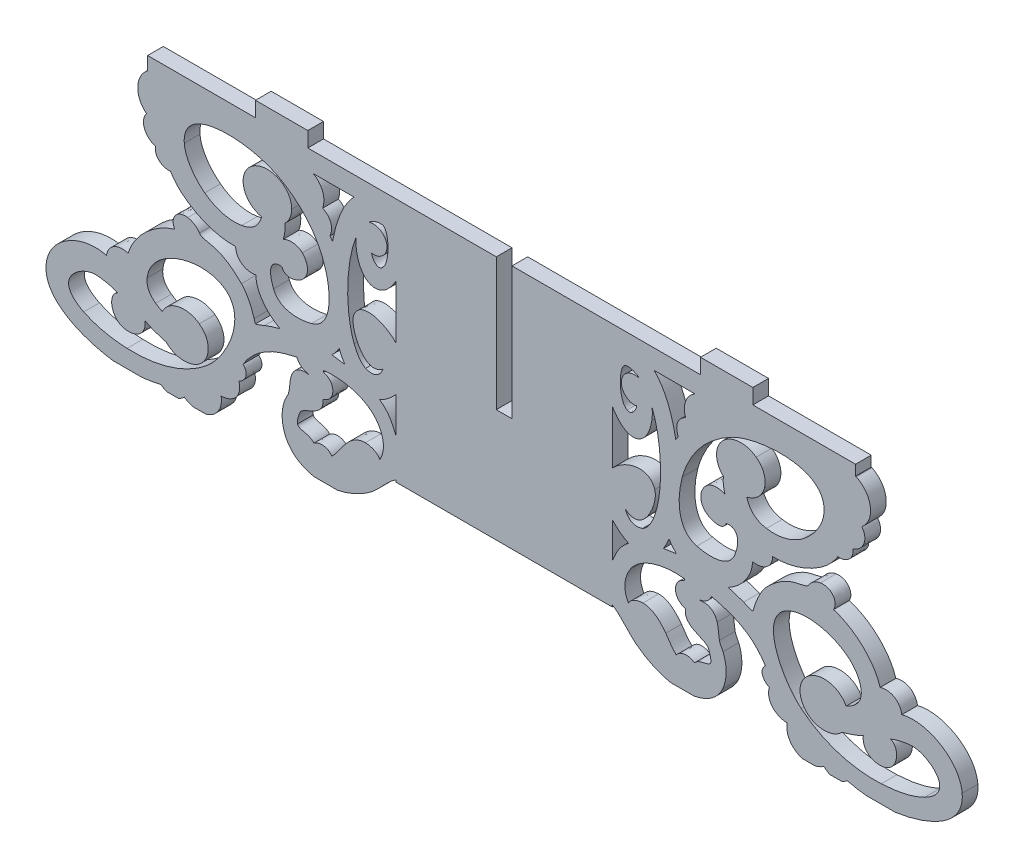
SolidWorks part; units mm, degrees
ref_plane "Plano frontal" through (0, 0, 0) normal (0, 0, 1) x (1, 0, 0)
ref_plane "Plano superior" through (0, 0, 0) normal (0, 1, 0) x (1, 0, 0)
ref_plane "Plano direito" through (0, 0, 0) normal (1, 0, 0) x (0, 0, -1)
sketch "Model" plane through (0, 0, 0) normal (0, 0, 1) x (1, 0, 0)
  line L0 (-5.6284, -112.7453) -> (-5.6464, -112.5024)
  line L1 (-13.1021, -117.3563) -> (-16.0542, -117.3569)
  line L2 (-18.281, -105.2638) -> (-19.6289, -105.6073)
  line L3 (-29.8849, -117.352) -> (-31.4771, -117.3528)
  line L4 (-33.3867, -117.362) -> (-34.8157, -117.362)
  line L5 (-37.9546, -117.362) -> (-41.6837, -117.3591)
  line L6 (-37.2753, -83.1991) -> (-37.2753, -81.5107)
  line L7 (-37.2753, -81.5107) -> (-23.5478, -81.5107)
  line L8 (-23.5478, -81.5107) -> (-23.5478, -79.5846)
  line L9 (-23.5478, -79.5846) -> (-16.8811, -79.5846)
  line L10 (-16.8811, -79.5846) -> (-16.8811, -81.5107)
  line L11 (-16.8811, -81.5107) -> (7.1189, -81.5107)
  line L12 (7.1189, -81.5107) -> (7.1189, -98.3678)
  line L13 (7.1189, -98.3678) -> (9.1189, -98.3678)
  line L14 (9.1189, -98.3678) -> (9.1189, -81.5107)
  line L15 (9.1189, -81.5107) -> (33.1189, -81.5107)
  line L16 (33.1189, -81.5107) -> (33.1189, -79.5846)
  line L17 (33.1189, -79.5846) -> (39.7856, -79.5846)
  line L18 (39.7856, -79.5846) -> (39.7856, -81.5107)
  line L19 (39.7856, -81.5107) -> (52.8602, -81.5107)
  line L20 (52.8602, -81.5107) -> (52.8602, -82.8287)
  line L21 (52.8602, -82.8287) -> (52.8959, -82.8287)
  line L22 (52.8959, -82.8287) -> (52.9623, -82.861)
  line L23 (57.9215, -117.3591) -> (54.1924, -117.362)
  line L24 (51.0535, -117.362) -> (49.6245, -117.362)
  line L25 (47.7148, -117.3528) -> (46.1226, -117.352)
  line L26 (35.8666, -105.6073) -> (34.5187, -105.2638)
  line L27 (32.2919, -117.3569) -> (29.3398, -117.3563)
  line L28 (21.8841, -112.5024) -> (21.8661, -112.7453)
  line L29 (-10.9876, -83.9801) -> (-16.2025, -83.9801)
  line L30 (32.4403, -83.9801) -> (27.2253, -83.9801)
  line L31 (21.8983, -107.6195) -> (21.8983, -103.0943)
  line L32 (21.8983, -97.4057) -> (21.8983, -90.5812)
  line L33 (30.061, -102.7829) -> (28.4015, -103.0293)
  line L34 (-5.6605, -107.6195) -> (-5.6605, -103.0943)
  line L35 (-5.6605, -97.4057) -> (-5.6605, -90.5812)
  line L36 (-13.8232, -102.7829) -> (-12.1638, -103.0293)
  spline S0 degree 3 poles (-5.6464, -112.5024) (-6.5419, -112.9865) (-7.8893, -114.6814) (-8.6517, -115.2757) knots 0.009901 0.009901 0.009901 0.009901 0.019802 0.019802 0.019802 0.019802
  spline S1 degree 3 poles (-8.6517, -115.2757) (-9.9492, -116.2871) (-11.4791, -117.04) (-13.1021, -117.3563) knots 0.019802 0.019802 0.019802 0.019802 0.029703 0.029703 0.029703 0.029703
  spline S2 degree 3 poles (-16.0542, -117.3569) (-17.6074, -117.0704) (-18.9753, -116.2771) (-19.6727, -114.8027) knots 0.039604 0.039604 0.039604 0.039604 0.049505 0.049505 0.049505 0.049505
  spline S3 degree 3 poles (-19.6727, -114.8027) (-20.2748, -113.5296) (-20.309, -111.9264) (-19.7445, -110.6272) knots 0.049505 0.049505 0.049505 0.049505 0.059406 0.059406 0.059406 0.059406
  spline S4 degree 3 poles (-19.7445, -110.6272) (-19.5924, -110.2771) (-19.3699, -109.9824) (-19.2888, -109.595) knots 0.059406 0.059406 0.059406 0.059406 0.069307 0.069307 0.069307 0.069307
  spline S5 degree 3 poles (-19.2888, -109.595) (-19.1614, -108.9856) (-19.1819, -108.3312) (-18.999, -107.7315) knots 0.069307 0.069307 0.069307 0.069307 0.079208 0.079208 0.079208 0.079208
  spline S6 degree 3 poles (-18.999, -107.7315) (-18.6689, -106.6497) (-17.8333, -106.246) (-16.8102, -106.4384) knots 0.079208 0.079208 0.079208 0.079208 0.089109 0.089109 0.089109 0.089109
  spline S7 degree 3 poles (-16.8102, -106.4384) (-16.8066, -106.4196) (-16.8024, -106.4007) (-16.7979, -106.3817) knots 0.089109 0.089109 0.089109 0.089109 0.09901 0.09901 0.09901 0.09901
  spline S8 degree 3 poles (-16.7979, -106.3817) (-17.4996, -106.2832) (-17.9964, -105.8964) (-18.281, -105.2638) knots 0.09901 0.09901 0.09901 0.09901 0.108911 0.108911 0.108911 0.108911
  spline S9 degree 3 poles (-19.6289, -105.6073) (-21.9055, -106.2199) (-23.8126, -107.3723) (-25.137, -109.472) knots 0.118812 0.118812 0.118812 0.118812 0.128713 0.128713 0.128713 0.128713
  spline S10 degree 3 poles (-25.137, -109.472) (-24.3471, -110.1811) (-24.768, -111.1844) (-25.6484, -111.6117) knots 0.128713 0.128713 0.128713 0.128713 0.138614 0.138614 0.138614 0.138614
  spline S11 degree 3 poles (-25.6484, -111.6117) (-25.2197, -113.1217) (-26.2828, -114.3014) (-27.9206, -114.3964) knots 0.138614 0.138614 0.138614 0.138614 0.148515 0.148515 0.148515 0.148515
  spline S12 degree 3 poles (-27.9206, -114.3964) (-27.6704, -115.807) (-28.5691, -117.0098) (-29.8849, -117.352) knots 0.148515 0.148515 0.148515 0.148515 0.158416 0.158416 0.158416 0.158416
  spline S13 degree 3 poles (-31.4771, -117.3528) (-31.8723, -117.2547) (-32.2526, -117.0856) (-32.6065, -116.8521) knots 0.168317 0.168317 0.168317 0.168317 0.178218 0.178218 0.178218 0.178218
  spline S14 degree 3 poles (-32.6065, -116.8521) (-32.7813, -117.0214) (-33.1597, -117.3166) (-33.3867, -117.362) knots 0.178218 0.178218 0.178218 0.178218 0.188119 0.188119 0.188119 0.188119
  spline S15 degree 3 poles (-34.8157, -117.362) (-35.0116, -117.3252) (-35.4128, -117.07) (-35.5882, -116.9422) knots 0.19802 0.19802 0.19802 0.19802 0.207921 0.207921 0.207921 0.207921
  spline S16 degree 3 poles (-35.5882, -116.9422) (-36.1338, -117.086) (-37.442, -117.3298) (-37.9546, -117.362) knots 0.207921 0.207921 0.207921 0.207921 0.217822 0.217822 0.217822 0.217822
  spline S17 degree 3 poles (-41.6837, -117.3591) (-44.9016, -116.9194) (-50.559, -115.1316) (-50.1979, -111.0071) knots 0.227723 0.227723 0.227723 0.227723 0.237624 0.237624 0.237624 0.237624
  spline S18 degree 3 poles (-50.1979, -111.0071) (-49.9051, -107.6597) (-45.7279, -105.3202) (-42.5097, -106.1811) knots 0.237624 0.237624 0.237624 0.237624 0.247525 0.247525 0.247525 0.247525
  spline S19 degree 3 poles (-42.5097, -106.1811) (-42.3406, -104.9368) (-41.1513, -104.1223) (-39.7553, -104.5529) knots 0.247525 0.247525 0.247525 0.247525 0.257426 0.257426 0.257426 0.257426
  spline S20 degree 3 poles (-39.7553, -104.5529) (-38.9652, -101.9343) (-36.3648, -99.6933) (-33.825, -98.9411) knots 0.257426 0.257426 0.257426 0.257426 0.267327 0.267327 0.267327 0.267327
  spline S21 degree 3 poles (-33.825, -98.9411) (-34.4145, -97.9132) (-33.6513, -96.6265) (-32.1639, -96.8236) knots 0.267327 0.267327 0.267327 0.267327 0.277228 0.277228 0.277228 0.277228
  spline S22 degree 3 poles (-32.1639, -96.8236) (-31.6489, -96.8918) (-30.977, -97.2747) (-30.6727, -97.7933) knots 0.277228 0.277228 0.277228 0.277228 0.287129 0.287129 0.287129 0.287129
  spline S23 degree 3 poles (-30.6727, -97.7933) (-30.2008, -98.5978) (-28.3124, -97.6373) (-25.3267, -100.6883) knots 0.287129 0.287129 0.287129 0.287129 0.29703 0.29703 0.29703 0.29703
  spline S24 degree 3 poles (-25.3267, -100.6883) (-24.602, -101.4287) (-24.0346, -102.6503) (-23.718, -103.7243) knots 0.29703 0.29703 0.29703 0.29703 0.306931 0.306931 0.306931 0.306931
  spline S25 degree 3 poles (-23.718, -103.7243) (-23.6918, -103.8135) (-23.611, -104.1406) (-23.5594, -104.2593) knots 0.306931 0.306931 0.306931 0.306931 0.316832 0.316832 0.316832 0.316832
  spline S26 degree 3 poles (-23.5594, -104.2593) (-23.2891, -104.2271) (-22.6447, -103.9373) (-22.3768, -103.8363) knots 0.316832 0.316832 0.316832 0.316832 0.326733 0.326733 0.326733 0.326733
  spline S27 degree 3 poles (-22.3768, -103.8363) (-21.7257, -103.591) (-21.0761, -103.3756) (-20.4179, -103.1989) knots 0.326733 0.326733 0.326733 0.326733 0.336634 0.336634 0.336634 0.336634
  spline S28 degree 3 poles (-20.4179, -103.1989) (-22.012, -102.3364) (-23.4449, -100.7002) (-23.5064, -98.8133) knots 0.336634 0.336634 0.336634 0.336634 0.346535 0.346535 0.346535 0.346535
  spline S29 degree 3 poles (-23.5064, -98.8133) (-24.7892, -99.0637) (-26.0243, -98.3309) (-26.0724, -96.9712) knots 0.346535 0.346535 0.346535 0.346535 0.356436 0.356436 0.356436 0.356436
  spline S30 degree 3 poles (-26.0724, -96.9712) (-28.4957, -97.0677) (-31.1466, -96.0514) (-32.9791, -94.4712) knots 0.356436 0.356436 0.356436 0.356436 0.366337 0.366337 0.366337 0.366337
  spline S31 degree 3 poles (-32.9791, -94.4712) (-33.492, -94.0288) (-33.9776, -93.4401) (-34.3711, -92.825) knots 0.366337 0.366337 0.366337 0.366337 0.376238 0.376238 0.376238 0.376238
  spline S32 degree 3 poles (-34.3711, -92.825) (-35.3634, -92.9517) (-36.4953, -92.1626) (-36.2723, -91.0278) knots 0.376238 0.376238 0.376238 0.376238 0.386139 0.386139 0.386139 0.386139
  spline S33 degree 3 poles (-36.2723, -91.0278) (-37.635, -90.5862) (-38.2812, -89.0905) (-37.4127, -87.9969) knots 0.386139 0.386139 0.386139 0.386139 0.39604 0.39604 0.39604 0.39604
  spline S34 degree 3 poles (-37.4127, -87.9969) (-39.0338, -86.6952) (-38.818, -84.3676) (-37.2753, -83.1991) knots 0.39604 0.39604 0.39604 0.39604 0.405941 0.405941 0.405941 0.405941
  spline S35 degree 3 poles (52.9623, -82.861) (54.9872, -83.848) (55.4482, -86.5534) (53.6504, -87.9969) knots 0.574257 0.574257 0.574257 0.574257 0.584158 0.584158 0.584158 0.584158
  spline S36 degree 3 poles (53.6504, -87.9969) (54.519, -89.0905) (53.8727, -90.5862) (52.5101, -91.0278) knots 0.584158 0.584158 0.584158 0.584158 0.594059 0.594059 0.594059 0.594059
  spline S37 degree 3 poles (52.5101, -91.0278) (52.733, -92.1626) (51.6012, -92.9517) (50.6088, -92.825) knots 0.594059 0.594059 0.594059 0.594059 0.60396 0.60396 0.60396 0.60396
  spline S38 degree 3 poles (50.6088, -92.825) (50.2153, -93.4401) (49.7298, -94.0288) (49.2168, -94.4712) knots 0.60396 0.60396 0.60396 0.60396 0.613861 0.613861 0.613861 0.613861
  spline S39 degree 3 poles (49.2168, -94.4712) (47.3843, -96.0514) (44.7334, -97.0677) (42.3101, -96.9712) knots 0.613861 0.613861 0.613861 0.613861 0.623762 0.623762 0.623762 0.623762
  spline S40 degree 3 poles (42.3101, -96.9712) (42.262, -98.3309) (41.027, -99.0637) (39.7442, -98.8133) knots 0.623762 0.623762 0.623762 0.623762 0.633663 0.633663 0.633663 0.633663
  spline S41 degree 3 poles (39.7442, -98.8133) (39.6827, -100.7002) (38.2497, -102.3364) (36.6556, -103.1989) knots 0.633663 0.633663 0.633663 0.633663 0.643564 0.643564 0.643564 0.643564
  spline S42 degree 3 poles (36.6556, -103.1989) (37.3138, -103.3756) (37.9634, -103.591) (38.6145, -103.8363) knots 0.643564 0.643564 0.643564 0.643564 0.653465 0.653465 0.653465 0.653465
  spline S43 degree 3 poles (38.6145, -103.8363) (38.8825, -103.9373) (39.5268, -104.2271) (39.7971, -104.2593) knots 0.653465 0.653465 0.653465 0.653465 0.663366 0.663366 0.663366 0.663366
  spline S44 degree 3 poles (39.7971, -104.2593) (39.8487, -104.1406) (39.9295, -103.8135) (39.9557, -103.7243) knots 0.663366 0.663366 0.663366 0.663366 0.673267 0.673267 0.673267 0.673267
  spline S45 degree 3 poles (39.9557, -103.7243) (40.2723, -102.6503) (40.8398, -101.4287) (41.5644, -100.6883) knots 0.673267 0.673267 0.673267 0.673267 0.683168 0.683168 0.683168 0.683168
  spline S46 degree 3 poles (41.5644, -100.6883) (44.5501, -97.6373) (46.4385, -98.5978) (46.9105, -97.7933) knots 0.683168 0.683168 0.683168 0.683168 0.693069 0.693069 0.693069 0.693069
  spline S47 degree 3 poles (46.9105, -97.7933) (47.2147, -97.2747) (47.8867, -96.8918) (48.4016, -96.8236) knots 0.693069 0.693069 0.693069 0.693069 0.70297 0.70297 0.70297 0.70297
  spline S48 degree 3 poles (48.4016, -96.8236) (49.8891, -96.6265) (50.6522, -97.9132) (50.0628, -98.9411) knots 0.70297 0.70297 0.70297 0.70297 0.712871 0.712871 0.712871 0.712871
  spline S49 degree 3 poles (50.0628, -98.9411) (52.6026, -99.6933) (55.2029, -101.9343) (55.9931, -104.5529) knots 0.712871 0.712871 0.712871 0.712871 0.722772 0.722772 0.722772 0.722772
  spline S50 degree 3 poles (55.9931, -104.5529) (57.389, -104.1223) (58.5783, -104.9368) (58.7475, -106.1811) knots 0.722772 0.722772 0.722772 0.722772 0.732673 0.732673 0.732673 0.732673
  spline S51 degree 3 poles (58.7475, -106.1811) (61.9656, -105.3202) (66.1428, -107.6597) (66.4357, -111.0071) knots 0.732673 0.732673 0.732673 0.732673 0.742574 0.742574 0.742574 0.742574
  spline S52 degree 3 poles (66.4357, -111.0071) (66.7967, -115.1316) (61.1393, -116.9194) (57.9215, -117.3591) knots 0.742574 0.742574 0.742574 0.742574 0.752475 0.752475 0.752475 0.752475
  spline S53 degree 3 poles (54.1924, -117.362) (53.6797, -117.3298) (52.3716, -117.086) (51.826, -116.9422) knots 0.762376 0.762376 0.762376 0.762376 0.772277 0.772277 0.772277 0.772277
  spline S54 degree 3 poles (51.826, -116.9422) (51.6505, -117.07) (51.2493, -117.3252) (51.0535, -117.362) knots 0.772277 0.772277 0.772277 0.772277 0.782178 0.782178 0.782178 0.782178
  spline S55 degree 3 poles (49.6245, -117.362) (49.3974, -117.3166) (49.019, -117.0214) (48.8442, -116.8521) knots 0.792079 0.792079 0.792079 0.792079 0.80198 0.80198 0.80198 0.80198
  spline S56 degree 3 poles (48.8442, -116.8521) (48.4903, -117.0856) (48.11, -117.2547) (47.7148, -117.3528) knots 0.80198 0.80198 0.80198 0.80198 0.811881 0.811881 0.811881 0.811881
  spline S57 degree 3 poles (46.1226, -117.352) (44.8069, -117.0098) (43.9081, -115.807) (44.1584, -114.3964) knots 0.821782 0.821782 0.821782 0.821782 0.831683 0.831683 0.831683 0.831683
  spline S58 degree 3 poles (44.1584, -114.3964) (42.5205, -114.3014) (41.4574, -113.1217) (41.8862, -111.6117) knots 0.831683 0.831683 0.831683 0.831683 0.841584 0.841584 0.841584 0.841584
  spline S59 degree 3 poles (41.8862, -111.6117) (41.0057, -111.1844) (40.5849, -110.1811) (41.3748, -109.472) knots 0.841584 0.841584 0.841584 0.841584 0.851485 0.851485 0.851485 0.851485
  spline S60 degree 3 poles (41.3748, -109.472) (40.0503, -107.3723) (38.1433, -106.2199) (35.8666, -105.6073) knots 0.851485 0.851485 0.851485 0.851485 0.861386 0.861386 0.861386 0.861386
  spline S61 degree 3 poles (34.5187, -105.2638) (34.2342, -105.8964) (33.7373, -106.2832) (33.0357, -106.3817) knots 0.871287 0.871287 0.871287 0.871287 0.881188 0.881188 0.881188 0.881188
  spline S62 degree 3 poles (33.0357, -106.3817) (33.0401, -106.4007) (33.0443, -106.4196) (33.048, -106.4384) knots 0.881188 0.881188 0.881188 0.881188 0.891089 0.891089 0.891089 0.891089
  spline S63 degree 3 poles (33.048, -106.4384) (34.071, -106.246) (34.9066, -106.6497) (35.2367, -107.7315) knots 0.891089 0.891089 0.891089 0.891089 0.90099 0.90099 0.90099 0.90099
  spline S64 degree 3 poles (35.2367, -107.7315) (35.4196, -108.3312) (35.3992, -108.9856) (35.5266, -109.595) knots 0.90099 0.90099 0.90099 0.90099 0.910891 0.910891 0.910891 0.910891
  spline S65 degree 3 poles (35.5266, -109.595) (35.6076, -109.9824) (35.8302, -110.2771) (35.9823, -110.6272) knots 0.910891 0.910891 0.910891 0.910891 0.920792 0.920792 0.920792 0.920792
  spline S66 degree 3 poles (35.9823, -110.6272) (36.5467, -111.9264) (36.5126, -113.5296) (35.9104, -114.8027) knots 0.920792 0.920792 0.920792 0.920792 0.930693 0.930693 0.930693 0.930693
  spline S67 degree 3 poles (35.9104, -114.8027) (35.2131, -116.2771) (33.8452, -117.0704) (32.2919, -117.3569) knots 0.930693 0.930693 0.930693 0.930693 0.940594 0.940594 0.940594 0.940594
  spline S68 degree 3 poles (29.3398, -117.3563) (27.7168, -117.04) (26.1869, -116.2871) (24.8894, -115.2757) knots 0.950495 0.950495 0.950495 0.950495 0.960396 0.960396 0.960396 0.960396
  spline S69 degree 3 poles (24.8894, -115.2757) (24.127, -114.6814) (22.7796, -112.9865) (21.8841, -112.5024) knots 0.960396 0.960396 0.960396 0.960396 0.970297 0.970297 0.970297 0.970297
  spline S70 degree 3 poles (21.8661, -112.7453) (12.8258, -112.7453) (3.4119, -112.7453) (-5.6284, -112.7453) knots 0.980198 0.980198 0.980198 0.980198 1 1 1 1
  spline S71 degree 3 poles (-16.2025, -83.9801) (-15.1507, -84.5589) (-14.5218, -85.7771) (-14.9827, -87.1985) knots 0 0 0 0 0.166667 0.166667 0.166667 0.166667
  spline S72 degree 3 poles (-14.9827, -87.1985) (-13.9248, -87.7097) (-13.6065, -88.7057) (-14.0462, -89.782) knots 0.166667 0.166667 0.166667 0.166667 0.333333 0.333333 0.333333 0.333333
  spline S73 degree 3 poles (-14.0462, -89.782) (-13.9394, -89.9313) (-13.8344, -90.0899) (-13.7323, -90.2521) knots 0.333333 0.333333 0.333333 0.333333 0.5 0.5 0.5 0.5
  spline S74 degree 3 poles (-13.7323, -90.2521) (-13.3251, -87.9243) (-12.4877, -85.4672) (-10.9876, -83.9801) knots 0.5 0.5 0.5 0.5 0.666667 0.666667 0.666667 0.666667
  spline S75 degree 3 poles (27.2253, -83.9801) (28.7254, -85.4672) (29.5629, -87.9243) (29.97, -90.2521) knots 0 0 0 0 0.166667 0.166667 0.166667 0.166667
  spline S76 degree 3 poles (29.97, -90.2521) (30.0721, -90.0899) (30.1772, -89.9313) (30.2839, -89.782) knots 0.166667 0.166667 0.166667 0.166667 0.333333 0.333333 0.333333 0.333333
  spline S77 degree 3 poles (30.2839, -89.782) (29.8442, -88.7057) (30.1626, -87.7097) (31.2204, -87.1985) knots 0.333333 0.333333 0.333333 0.333333 0.5 0.5 0.5 0.5
  spline S78 degree 3 poles (31.2204, -87.1985) (30.7596, -85.7771) (31.3885, -84.5589) (32.4403, -83.9801) knots 0.5 0.5 0.5 0.5 0.666667 0.666667 0.666667 0.666667
  spline S79 degree 3 poles (21.8983, -103.0943) (22.4767, -103.7415) (23.2107, -104.3434) (23.9781, -104.6802) knots 0.25 0.25 0.25 0.25 0.5 0.5 0.5 0.5
  spline S80 degree 3 poles (23.9781, -104.6802) (22.8318, -105.493) (22.4114, -106.3816) (21.8983, -107.6195) knots 0.5 0.5 0.5 0.5 1 1 1 1
  spline S81 degree 3 poles (23.5508, -101.1004) (23.9717, -101.4816) (24.5568, -101.6481) (25.0819, -101.5176) knots 0 0 0 0 0.090909 0.090909 0.090909 0.090909
  spline S82 degree 3 poles (25.0819, -101.5176) (26.5124, -101.1622) (27.6791, -98.283) (27.2955, -97.0934) knots 0.090909 0.090909 0.090909 0.090909 0.181818 0.181818 0.181818 0.181818
  spline S83 degree 3 poles (27.2955, -97.0934) (26.5745, -94.8575) (23.4797, -95.7308) (21.8983, -97.4057) knots 0.181818 0.181818 0.181818 0.181818 0.272727 0.272727 0.272727 0.272727
  spline S84 degree 3 poles (21.8983, -90.5812) (23.715, -93.8349) (26.3849, -93.1363) (26.9173, -89.6854) knots 0.363636 0.363636 0.363636 0.363636 0.454545 0.454545 0.454545 0.454545
  spline S85 degree 3 poles (26.9173, -89.6854) (26.9939, -89.1892) (27.0085, -88.6836) (26.9564, -88.2068) knots 0.454545 0.454545 0.454545 0.454545 0.545455 0.545455 0.545455 0.545455
  spline S86 degree 3 poles (26.9564, -88.2068) (28.2487, -91.4505) (28.451, -96.9108) (27.213, -100.145) knots 0.545455 0.545455 0.545455 0.545455 0.636364 0.636364 0.636364 0.636364
  spline S87 degree 3 poles (27.213, -100.145) (26.9098, -100.9371) (26.4428, -101.7745) (25.7631, -102.1337) knots 0.636364 0.636364 0.636364 0.636364 0.727273 0.727273 0.727273 0.727273
  spline S88 degree 3 poles (25.7631, -102.1337) (25.054, -102.3989) (24.3, -102.3651) (23.8014, -101.6136) knots 0.727273 0.727273 0.727273 0.727273 0.818182 0.818182 0.818182 0.818182
  spline S89 degree 3 poles (23.8014, -101.6136) (23.6985, -101.4585) (23.6152, -101.2845) (23.5508, -101.1004) knots 0.818182 0.818182 0.818182 0.818182 1 1 1 1
  spline S90 degree 3 poles (25.3652, -85.8031) (23.4778, -85.2427) (22.2258, -87.425) (23.6524, -88.664) knots 0 0 0 0 0.166667 0.166667 0.166667 0.166667
  spline S91 degree 3 poles (23.6524, -88.664) (24.0428, -89.0031) (24.532, -89.1242) (25.0001, -89.0115) knots 0.166667 0.166667 0.166667 0.166667 0.333333 0.333333 0.333333 0.333333
  spline S92 degree 3 poles (25.0001, -89.0115) (24.9505, -89.519) (24.3805, -90.3951) (23.7771, -90.072) knots 0.333333 0.333333 0.333333 0.333333 0.5 0.5 0.5 0.5
  spline S93 degree 3 poles (23.7771, -90.072) (22.6078, -89.4459) (22.6642, -85.3539) (23.6446, -85.2345) knots 0.5 0.5 0.5 0.5 0.666667 0.666667 0.666667 0.666667
  spline S94 degree 3 poles (23.6446, -85.2345) (24.2518, -85.1606) (24.8926, -85.4231) (25.3652, -85.8031) knots 0.666667 0.666667 0.666667 0.666667 1 1 1 1
  spline S95 degree 3 poles (28.4015, -103.0293) (28.6801, -102.5939) (28.9165, -102.111) (29.1159, -101.617) knots 0.25 0.25 0.25 0.25 0.5 0.5 0.5 0.5
  spline S96 degree 3 poles (29.1159, -101.617) (29.3835, -102.0615) (29.6983, -102.454) (30.061, -102.7829) knots 0.5 0.5 0.5 0.5 1 1 1 1
  spline S97 degree 3 poles (36.0381, -91.2717) (35.9571, -91.9263) (36.0478, -92.518) (36.2461, -93.1381) knots 0 0 0 0 0.058824 0.058824 0.058824 0.058824
  spline S98 degree 3 poles (36.2461, -93.1381) (35.4573, -92.77) (34.4529, -92.7857) (33.8083, -93.4305) knots 0.058824 0.058824 0.058824 0.058824 0.117647 0.117647 0.117647 0.117647
  spline S99 degree 3 poles (33.8083, -93.4305) (32.824, -94.4151) (32.906, -96.043) (34.3932, -96.72) knots 0.117647 0.117647 0.117647 0.117647 0.176471 0.176471 0.176471 0.176471
  spline S100 degree 3 poles (34.3932, -96.72) (35.0481, -97.0182) (36.1044, -97.1431) (36.38, -96.2826) knots 0.176471 0.176471 0.176471 0.176471 0.235294 0.235294 0.235294 0.235294
  spline S101 degree 3 poles (36.38, -96.2826) (36.7529, -96.1892) (37.1846, -96.2244) (37.4917, -96.5126) knots 0.235294 0.235294 0.235294 0.235294 0.294118 0.294118 0.294118 0.294118
  spline S102 degree 3 poles (37.4917, -96.5126) (38.1562, -97.136) (37.7715, -98.4847) (37.4787, -99.2187) knots 0.294118 0.294118 0.294118 0.294118 0.352941 0.352941 0.352941 0.352941
  spline S103 degree 3 poles (37.4787, -99.2187) (36.7026, -101.1641) (34.098, -101.0219) (32.653, -100.6401) knots 0.352941 0.352941 0.352941 0.352941 0.411765 0.411765 0.411765 0.411765
  spline S104 degree 3 poles (32.653, -100.6401) (29.9072, -99.9146) (30.2036, -96.0743) (30.8, -93.9515) knots 0.411765 0.411765 0.411765 0.411765 0.470588 0.470588 0.470588 0.470588
  spline S105 degree 3 poles (30.8, -93.9515) (31.8304, -90.2843) (34.2859, -87.8629) (37.1386, -86.3959) knots 0.470588 0.470588 0.470588 0.470588 0.529412 0.529412 0.529412 0.529412
  spline S106 degree 3 poles (37.1386, -86.3959) (40.7014, -84.5637) (49.1984, -84.0674) (48.8428, -88.8376) knots 0.529412 0.529412 0.529412 0.529412 0.588235 0.588235 0.588235 0.588235
  spline S107 degree 3 poles (48.8428, -88.8376) (48.7201, -90.4835) (47.4807, -92.0612) (46.2401, -93.0183) knots 0.588235 0.588235 0.588235 0.588235 0.647059 0.647059 0.647059 0.647059
  spline S108 degree 3 poles (46.2401, -93.0183) (44.8579, -94.0846) (43.1427, -94.5336) (41.5242, -94.2588) knots 0.647059 0.647059 0.647059 0.647059 0.705882 0.705882 0.705882 0.705882
  spline S109 degree 3 poles (41.5242, -94.2588) (40.1542, -94.0262) (39.3691, -93.3149) (39.004, -92.0517) knots 0.705882 0.705882 0.705882 0.705882 0.764706 0.764706 0.764706 0.764706
  spline S110 degree 3 poles (39.004, -92.0517) (41.467, -91.4795) (42.2002, -88.5442) (40.2066, -87.0616) knots 0.764706 0.764706 0.764706 0.764706 0.823529 0.823529 0.823529 0.823529
  spline S111 degree 3 poles (40.2066, -87.0616) (38.2649, -85.6175) (35.1699, -86.7953) (35.1699, -89.2835) knots 0.823529 0.823529 0.823529 0.823529 0.882353 0.882353 0.882353 0.882353
  spline S112 degree 3 poles (35.1699, -89.2835) (35.1699, -90.0978) (35.5296, -90.7871) (36.0381, -91.2717) knots 0.882353 0.882353 0.882353 0.882353 1 1 1 1
  spline S113 degree 3 poles (51.1493, -111.9298) (52.1053, -111.631) (53.0002, -111.4234) (53.8539, -110.903) knots 0 0 0 0 0.066667 0.066667 0.066667 0.066667
  spline S114 degree 3 poles (53.8539, -110.903) (53.6479, -112.4349) (54.9122, -113.3124) (56.3066, -113.1246) knots 0.066667 0.066667 0.066667 0.066667 0.133333 0.133333 0.133333 0.133333
  spline S115 degree 3 poles (56.3066, -113.1246) (58.3124, -112.8546) (58.6016, -110.0741) (57.3006, -109.5954) knots 0.133333 0.133333 0.133333 0.133333 0.2 0.2 0.2 0.2
  spline S116 degree 3 poles (57.3006, -109.5954) (58.0363, -109.2558) (59.5416, -108.9265) (60.365, -108.991) knots 0.2 0.2 0.2 0.2 0.266667 0.266667 0.266667 0.266667
  spline S117 degree 3 poles (60.365, -108.991) (62.3074, -109.1432) (65.7576, -111.784) (61.6432, -113.8456) knots 0.266667 0.266667 0.266667 0.266667 0.333333 0.333333 0.333333 0.333333
  spline S118 degree 3 poles (61.6432, -113.8456) (59.9784, -114.6796) (57.9677, -115.026) (56.1294, -115.1075) knots 0.333333 0.333333 0.333333 0.333333 0.4 0.4 0.4 0.4
  spline S119 degree 3 poles (56.1294, -115.1075) (52.5719, -115.2653) (48.9495, -114.3726) (45.962, -111.9195) knots 0.4 0.4 0.4 0.4 0.466667 0.466667 0.466667 0.466667
  spline S120 degree 3 poles (45.962, -111.9195) (43.1531, -109.6131) (39.8805, -102.7247) (45.4357, -101.5909) knots 0.466667 0.466667 0.466667 0.466667 0.533333 0.533333 0.533333 0.533333
  spline S121 degree 3 poles (45.4357, -101.5909) (48.3962, -100.9867) (53.1811, -102.7176) (53.572, -106.0571) knots 0.533333 0.533333 0.533333 0.533333 0.6 0.6 0.6 0.6
  spline S122 degree 3 poles (53.572, -106.0571) (53.6908, -107.072) (53.2531, -107.7524) (52.4812, -108.3091) knots 0.6 0.6 0.6 0.6 0.666667 0.666667 0.666667 0.666667
  spline S123 degree 3 poles (52.4812, -108.3091) (52.2802, -108.4541) (51.9406, -108.6729) (51.655, -108.7981) knots 0.666667 0.666667 0.666667 0.666667 0.733333 0.733333 0.733333 0.733333
  spline S124 degree 3 poles (51.655, -108.7981) (50.7762, -107.0507) (48.3934, -106.7193) (46.935, -107.804) knots 0.733333 0.733333 0.733333 0.733333 0.8 0.8 0.8 0.8
  spline S125 degree 3 poles (46.935, -107.804) (44.6881, -109.4749) (45.9755, -112.8551) (48.8706, -112.8551) knots 0.8 0.8 0.8 0.8 0.866667 0.866667 0.866667 0.866667
  spline S126 degree 3 poles (48.8706, -112.8551) (49.6737, -112.8551) (50.5239, -112.5649) (51.1493, -111.9298) knots 0.866667 0.866667 0.866667 0.866667 1 1 1 1
  spline S127 degree 3 poles (23.9524, -111.2867) (23.2017, -109.9941) (23.4088, -108.6086) (24.2064, -107.3907) knots 0 0 0 0 0.083333 0.083333 0.083333 0.083333
  spline S128 degree 3 poles (24.2064, -107.3907) (25.5334, -105.3641) (28.7512, -104.7117) (31.1004, -105.0405) knots 0.083333 0.083333 0.083333 0.083333 0.166667 0.166667 0.166667 0.166667
  spline S129 degree 3 poles (31.1004, -105.0405) (31.0988, -105.1097) (31.1027, -105.1789) (31.1118, -105.2473) knots 0.166667 0.166667 0.166667 0.166667 0.25 0.25 0.25 0.25
  spline S130 degree 3 poles (31.1118, -105.2473) (29.5784, -105.6147) (29.4562, -107.7696) (31.2042, -108.2724) knots 0.25 0.25 0.25 0.25 0.333333 0.333333 0.333333 0.333333
  spline S131 degree 3 poles (31.2042, -108.2724) (30.9074, -110.2656) (33.7456, -110.3479) (34.1184, -111.1592) knots 0.333333 0.333333 0.333333 0.333333 0.416667 0.416667 0.416667 0.416667
  spline S132 degree 3 poles (34.1184, -111.1592) (34.2574, -111.4616) (34.5133, -112.2393) (34.4225, -112.5848) knots 0.416667 0.416667 0.416667 0.416667 0.5 0.5 0.5 0.5
  spline S133 degree 3 poles (34.4225, -112.5848) (34.2683, -113.1709) (32.9564, -112.8985) (32.3438, -113.6709) knots 0.5 0.5 0.5 0.5 0.583333 0.583333 0.583333 0.583333
  spline S134 degree 3 poles (32.3438, -113.6709) (31.642, -113.1418) (30.5964, -113.2095) (30.045, -113.9512) knots 0.583333 0.583333 0.583333 0.583333 0.666667 0.666667 0.666667 0.666667
  spline S135 degree 3 poles (30.045, -113.9512) (29.416, -113.3706) (29.1977, -112.8867) (28.7045, -112.2302) knots 0.666667 0.666667 0.666667 0.666667 0.75 0.75 0.75 0.75
  spline S136 degree 3 poles (28.7045, -112.2302) (28.0003, -111.2928) (27.0428, -110.3218) (25.7952, -110.3477) knots 0.75 0.75 0.75 0.75 0.833333 0.833333 0.833333 0.833333
  spline S137 degree 3 poles (25.7952, -110.3477) (25.1347, -110.3613) (24.2483, -110.6349) (23.9524, -111.2867) knots 0.833333 0.833333 0.833333 0.833333 1 1 1 1
  spline S138 degree 3 poles (-5.6605, -103.0943) (-6.239, -103.7415) (-6.9729, -104.3434) (-7.7404, -104.6802) knots 0.25 0.25 0.25 0.25 0.5 0.5 0.5 0.5
  spline S139 degree 3 poles (-7.7404, -104.6802) (-6.5941, -105.493) (-6.1737, -106.3816) (-5.6605, -107.6195) knots 0.5 0.5 0.5 0.5 1 1 1 1
  spline S140 degree 3 poles (-7.3131, -101.1004) (-7.734, -101.4816) (-8.3191, -101.6481) (-8.8441, -101.5176) knots 0 0 0 0 0.090909 0.090909 0.090909 0.090909
  spline S141 degree 3 poles (-8.8441, -101.5176) (-10.2747, -101.1622) (-11.4413, -98.283) (-11.0577, -97.0934) knots 0.090909 0.090909 0.090909 0.090909 0.181818 0.181818 0.181818 0.181818
  spline S142 degree 3 poles (-11.0577, -97.0934) (-10.3368, -94.8575) (-7.2419, -95.7308) (-5.6605, -97.4057) knots 0.181818 0.181818 0.181818 0.181818 0.272727 0.272727 0.272727 0.272727
  spline S143 degree 3 poles (-5.6605, -90.5812) (-7.4773, -93.8349) (-10.1472, -93.1363) (-10.6795, -89.6854) knots 0.363636 0.363636 0.363636 0.363636 0.454545 0.454545 0.454545 0.454545
  spline S144 degree 3 poles (-10.6795, -89.6854) (-10.7561, -89.1892) (-10.7708, -88.6836) (-10.7187, -88.2068) knots 0.454545 0.454545 0.454545 0.454545 0.545455 0.545455 0.545455 0.545455
  spline S145 degree 3 poles (-10.7187, -88.2068) (-12.011, -91.4505) (-12.2132, -96.9108) (-10.9753, -100.145) knots 0.545455 0.545455 0.545455 0.545455 0.636364 0.636364 0.636364 0.636364
  spline S146 degree 3 poles (-10.9753, -100.145) (-10.6721, -100.9371) (-10.205, -101.7745) (-9.5254, -102.1337) knots 0.636364 0.636364 0.636364 0.636364 0.727273 0.727273 0.727273 0.727273
  spline S147 degree 3 poles (-9.5254, -102.1337) (-8.8163, -102.3989) (-8.0623, -102.3651) (-7.5637, -101.6136) knots 0.727273 0.727273 0.727273 0.727273 0.818182 0.818182 0.818182 0.818182
  spline S148 degree 3 poles (-7.5637, -101.6136) (-7.4608, -101.4585) (-7.3775, -101.2845) (-7.3131, -101.1004) knots 0.818182 0.818182 0.818182 0.818182 1 1 1 1
  spline S149 degree 3 poles (-9.1275, -85.8031) (-7.2401, -85.2427) (-5.9881, -87.425) (-7.4147, -88.664) knots 0 0 0 0 0.166667 0.166667 0.166667 0.166667
  spline S150 degree 3 poles (-7.4147, -88.664) (-7.805, -89.0031) (-8.2942, -89.1242) (-8.7624, -89.0115) knots 0.166667 0.166667 0.166667 0.166667 0.333333 0.333333 0.333333 0.333333
  spline S151 degree 3 poles (-8.7624, -89.0115) (-8.7128, -89.519) (-8.1428, -90.3951) (-7.5394, -90.072) knots 0.333333 0.333333 0.333333 0.333333 0.5 0.5 0.5 0.5
  spline S152 degree 3 poles (-7.5394, -90.072) (-6.3701, -89.4459) (-6.4265, -85.3539) (-7.4069, -85.2345) knots 0.5 0.5 0.5 0.5 0.666667 0.666667 0.666667 0.666667
  spline S153 degree 3 poles (-7.4069, -85.2345) (-8.014, -85.1606) (-8.6549, -85.4231) (-9.1275, -85.8031) knots 0.666667 0.666667 0.666667 0.666667 1 1 1 1
  spline S154 degree 3 poles (-12.1638, -103.0293) (-12.4424, -102.5939) (-12.6788, -102.111) (-12.8781, -101.617) knots 0.25 0.25 0.25 0.25 0.5 0.5 0.5 0.5
  spline S155 degree 3 poles (-12.8781, -101.617) (-13.1457, -102.0615) (-13.4606, -102.454) (-13.8232, -102.7829) knots 0.5 0.5 0.5 0.5 1 1 1 1
  spline S156 degree 3 poles (-19.8004, -91.2717) (-19.7193, -91.9263) (-19.81, -92.518) (-20.0084, -93.1381) knots 0 0 0 0 0.058824 0.058824 0.058824 0.058824
  spline S157 degree 3 poles (-20.0084, -93.1381) (-19.2196, -92.77) (-18.2152, -92.7857) (-17.5705, -93.4305) knots 0.058824 0.058824 0.058824 0.058824 0.117647 0.117647 0.117647 0.117647
  spline S158 degree 3 poles (-17.5705, -93.4305) (-16.5862, -94.4151) (-16.6682, -96.043) (-18.1554, -96.72) knots 0.117647 0.117647 0.117647 0.117647 0.176471 0.176471 0.176471 0.176471
  spline S159 degree 3 poles (-18.1554, -96.72) (-18.8104, -97.0182) (-19.8667, -97.1431) (-20.1422, -96.2826) knots 0.176471 0.176471 0.176471 0.176471 0.235294 0.235294 0.235294 0.235294
  spline S160 degree 3 poles (-20.1422, -96.2826) (-20.5152, -96.1892) (-20.9468, -96.2244) (-21.254, -96.5126) knots 0.235294 0.235294 0.235294 0.235294 0.294118 0.294118 0.294118 0.294118
  spline S161 degree 3 poles (-21.254, -96.5126) (-21.9184, -97.136) (-21.5338, -98.4847) (-21.2409, -99.2187) knots 0.294118 0.294118 0.294118 0.294118 0.352941 0.352941 0.352941 0.352941
  spline S162 degree 3 poles (-21.2409, -99.2187) (-20.4648, -101.1641) (-17.8602, -101.0219) (-16.4152, -100.6401) knots 0.352941 0.352941 0.352941 0.352941 0.411765 0.411765 0.411765 0.411765
  spline S163 degree 3 poles (-16.4152, -100.6401) (-13.6695, -99.9146) (-13.9659, -96.0743) (-14.5623, -93.9515) knots 0.411765 0.411765 0.411765 0.411765 0.470588 0.470588 0.470588 0.470588
  spline S164 degree 3 poles (-14.5623, -93.9515) (-15.5927, -90.2843) (-18.0482, -87.8629) (-20.9008, -86.3959) knots 0.470588 0.470588 0.470588 0.470588 0.529412 0.529412 0.529412 0.529412
  spline S165 degree 3 poles (-20.9008, -86.3959) (-24.4637, -84.5637) (-32.9607, -84.0674) (-32.6051, -88.8376) knots 0.529412 0.529412 0.529412 0.529412 0.588235 0.588235 0.588235 0.588235
  spline S166 degree 3 poles (-32.6051, -88.8376) (-32.4823, -90.4835) (-31.2429, -92.0612) (-30.0023, -93.0183) knots 0.588235 0.588235 0.588235 0.588235 0.647059 0.647059 0.647059 0.647059
  spline S167 degree 3 poles (-30.0023, -93.0183) (-28.6202, -94.0846) (-26.905, -94.5336) (-25.2865, -94.2588) knots 0.647059 0.647059 0.647059 0.647059 0.705882 0.705882 0.705882 0.705882
  spline S168 degree 3 poles (-25.2865, -94.2588) (-23.9165, -94.0262) (-23.1313, -93.3149) (-22.7663, -92.0517) knots 0.705882 0.705882 0.705882 0.705882 0.764706 0.764706 0.764706 0.764706
  spline S169 degree 3 poles (-22.7663, -92.0517) (-25.2292, -91.4795) (-25.9624, -88.5442) (-23.9688, -87.0616) knots 0.764706 0.764706 0.764706 0.764706 0.823529 0.823529 0.823529 0.823529
  spline S170 degree 3 poles (-23.9688, -87.0616) (-22.0271, -85.6175) (-18.9321, -86.7953) (-18.9321, -89.2835) knots 0.823529 0.823529 0.823529 0.823529 0.882353 0.882353 0.882353 0.882353
  spline S171 degree 3 poles (-18.9321, -89.2835) (-18.9321, -90.0978) (-19.2919, -90.7871) (-19.8004, -91.2717) knots 0.882353 0.882353 0.882353 0.882353 1 1 1 1
  spline S172 degree 3 poles (-34.9116, -111.9298) (-35.8675, -111.631) (-36.7624, -111.4234) (-37.6162, -110.903) knots 0 0 0 0 0.066667 0.066667 0.066667 0.066667
  spline S173 degree 3 poles (-37.6162, -110.903) (-37.4102, -112.4349) (-38.6744, -113.3124) (-40.0688, -113.1246) knots 0.066667 0.066667 0.066667 0.066667 0.133333 0.133333 0.133333 0.133333
  spline S174 degree 3 poles (-40.0688, -113.1246) (-42.0746, -112.8546) (-42.3638, -110.0741) (-41.0629, -109.5954) knots 0.133333 0.133333 0.133333 0.133333 0.2 0.2 0.2 0.2
  spline S175 degree 3 poles (-41.0629, -109.5954) (-41.7985, -109.2558) (-43.3038, -108.9265) (-44.1273, -108.991) knots 0.2 0.2 0.2 0.2 0.266667 0.266667 0.266667 0.266667
  spline S176 degree 3 poles (-44.1273, -108.991) (-46.0697, -109.1432) (-49.5199, -111.784) (-45.4055, -113.8456) knots 0.266667 0.266667 0.266667 0.266667 0.333333 0.333333 0.333333 0.333333
  spline S177 degree 3 poles (-45.4055, -113.8456) (-43.7407, -114.6796) (-41.7299, -115.026) (-39.8917, -115.1075) knots 0.333333 0.333333 0.333333 0.333333 0.4 0.4 0.4 0.4
  spline S178 degree 3 poles (-39.8917, -115.1075) (-36.3342, -115.2653) (-32.7117, -114.3726) (-29.7243, -111.9195) knots 0.4 0.4 0.4 0.4 0.466667 0.466667 0.466667 0.466667
  spline S179 degree 3 poles (-29.7243, -111.9195) (-26.9154, -109.6131) (-23.6427, -102.7247) (-29.198, -101.5909) knots 0.466667 0.466667 0.466667 0.466667 0.533333 0.533333 0.533333 0.533333
  spline S180 degree 3 poles (-29.198, -101.5909) (-32.1585, -100.9867) (-36.9434, -102.7176) (-37.3343, -106.0571) knots 0.533333 0.533333 0.533333 0.533333 0.6 0.6 0.6 0.6
  spline S181 degree 3 poles (-37.3343, -106.0571) (-37.4531, -107.072) (-37.0154, -107.7524) (-36.2434, -108.3091) knots 0.6 0.6 0.6 0.6 0.666667 0.666667 0.666667 0.666667
  spline S182 degree 3 poles (-36.2434, -108.3091) (-36.0425, -108.4541) (-35.7029, -108.6729) (-35.4172, -108.7981) knots 0.666667 0.666667 0.666667 0.666667 0.733333 0.733333 0.733333 0.733333
  spline S183 degree 3 poles (-35.4172, -108.7981) (-34.5385, -107.0507) (-32.1557, -106.7193) (-30.6972, -107.804) knots 0.733333 0.733333 0.733333 0.733333 0.8 0.8 0.8 0.8
  spline S184 degree 3 poles (-30.6972, -107.804) (-28.4504, -109.4749) (-29.7377, -112.8551) (-32.6329, -112.8551) knots 0.8 0.8 0.8 0.8 0.866667 0.866667 0.866667 0.866667
  spline S185 degree 3 poles (-32.6329, -112.8551) (-33.4359, -112.8551) (-34.2861, -112.5649) (-34.9116, -111.9298) knots 0.866667 0.866667 0.866667 0.866667 1 1 1 1
  spline S186 degree 3 poles (-7.7147, -111.2867) (-6.9639, -109.9941) (-7.1711, -108.6086) (-7.9686, -107.3907) knots 0 0 0 0 0.083333 0.083333 0.083333 0.083333
  spline S187 degree 3 poles (-7.9686, -107.3907) (-9.2957, -105.3641) (-12.5134, -104.7117) (-14.8627, -105.0405) knots 0.083333 0.083333 0.083333 0.083333 0.166667 0.166667 0.166667 0.166667
  spline S188 degree 3 poles (-14.8627, -105.0405) (-14.8611, -105.1097) (-14.865, -105.1789) (-14.8741, -105.2473) knots 0.166667 0.166667 0.166667 0.166667 0.25 0.25 0.25 0.25
  spline S189 degree 3 poles (-14.8741, -105.2473) (-13.3407, -105.6147) (-13.2185, -107.7696) (-14.9665, -108.2724) knots 0.25 0.25 0.25 0.25 0.333333 0.333333 0.333333 0.333333
  spline S190 degree 3 poles (-14.9665, -108.2724) (-14.6696, -110.2656) (-17.5079, -110.3479) (-17.8806, -111.1592) knots 0.333333 0.333333 0.333333 0.333333 0.416667 0.416667 0.416667 0.416667
  spline S191 degree 3 poles (-17.8806, -111.1592) (-18.0197, -111.4616) (-18.2756, -112.2393) (-18.1847, -112.5848) knots 0.416667 0.416667 0.416667 0.416667 0.5 0.5 0.5 0.5
  spline S192 degree 3 poles (-18.1847, -112.5848) (-18.0306, -113.1709) (-16.7186, -112.8985) (-16.106, -113.6709) knots 0.5 0.5 0.5 0.5 0.583333 0.583333 0.583333 0.583333
  spline S193 degree 3 poles (-16.106, -113.6709) (-15.4043, -113.1418) (-14.3587, -113.2095) (-13.8072, -113.9512) knots 0.583333 0.583333 0.583333 0.583333 0.666667 0.666667 0.666667 0.666667
  spline S194 degree 3 poles (-13.8072, -113.9512) (-13.1783, -113.3706) (-12.9599, -112.8867) (-12.4668, -112.2302) knots 0.666667 0.666667 0.666667 0.666667 0.75 0.75 0.75 0.75
  spline S195 degree 3 poles (-12.4668, -112.2302) (-11.7626, -111.2928) (-10.8051, -110.3218) (-9.5574, -110.3477) knots 0.75 0.75 0.75 0.75 0.833333 0.833333 0.833333 0.833333
  spline S196 degree 3 poles (-9.5574, -110.3477) (-8.897, -110.3613) (-8.0106, -110.6349) (-7.7147, -111.2867) knots 0.833333 0.833333 0.833333 0.833333 1 1 1 1
extrude "Ressalto-extrusão1" add sketch "Model" along normal blind 2
